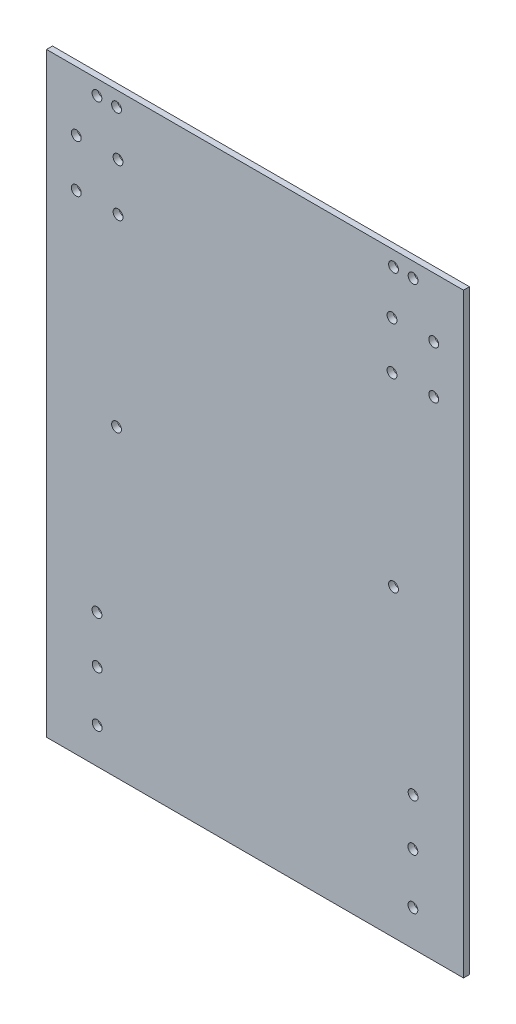
SolidWorks part; units mm, degrees
ref_plane "前视基准面" through (0, 0, 0) normal (0, 0, 1) x (1, 0, 0)
ref_plane "上视基准面" through (0, 0, 0) normal (0, 1, 0) x (1, 0, 0)
ref_plane "右视基准面" through (0, 0, 0) normal (1, 0, 0) x (0, 0, -1)
sketch "草图1" plane through (0, 0, 0) normal (0, 0, 1) x (1, 0, 0)
  line L1 (-34.1847, 39.4892) -> (105.8153, 39.4892)
  line L2 (-34.1847, 39.4892) -> (-34.1847, -160.5108)
  line L3 (-34.1847, -160.5108) -> (105.8153, -160.5108)
  line L4 (105.8153, 39.4892) -> (105.8153, -160.5108)
  dimension "D1" = 140
  dimension "D2" = 200
extrude "凸台-拉伸1" add sketch "草图1" along normal blind 2
sketch "草图3" plane through (0, 0, 2) normal (0, 0, 1) x (1, 0, 0)
  line L0 (35.8153, 55.5197) -> (35.8153, -164.492) construction
  line L1 (105.8153, 39.4892) -> (-34.1847, 39.4892) construction
  line L2 (127.7344, -12.0108) -> (-49.852, -12.0108) construction
  line L3 (-24.1847, 19.4892) -> (-10.1847, 19.4892) construction
  line L4 (-59.4781, -58.5108) -> (127.7344, -58.5108) construction
  line L5 (-34.1847, 39.4892) -> (-34.1847, -160.5108) construction
  line L6 (-17.1847, 7.5928) -> (-17.1847, -161.4246) construction
  circle A0 centre (-10.6847, 34.4892) radius 1.65
  circle A1 centre (82.3153, 34.4892) radius 1.65
  circle A2 centre (82.3153, -58.5108) radius 1.65
  circle A3 centre (-10.6847, -58.5108) radius 1.65
  circle A4 centre (-24.1847, 19.4892) radius 1.65
  circle A5 centre (-10.1847, 19.4892) radius 1.65
  circle A6 centre (-24.1847, 3.4892) radius 1.65
  circle A7 centre (-10.1847, 3.4892) radius 1.65
  circle A8 centre (81.8153, 3.4892) radius 1.65
  circle A9 centre (95.8153, 3.4892) radius 1.65
  circle A10 centre (81.8153, 19.4892) radius 1.65
  circle A11 centre (95.8153, 19.4892) radius 1.65
  circle A12 centre (-17.1847, -131.5108) radius 1.65
  circle A13 centre (-17.1847, -148.5108) radius 1.65
  circle A14 centre (88.8153, -148.5108) radius 1.65
  circle A15 centre (88.8153, -131.5108) radius 1.65
  circle A16 centre (-17.2547, 34.4892) radius 1.65
  circle A17 centre (88.8853, 34.4892) radius 1.65
  circle A18 centre (88.8853, -115.7208) radius 1.65
  circle A19 centre (-17.2547, -115.7208) radius 1.65
  dimension "D1" = 3.3
  dimension "D5" = 3.3
  dimension "D6" = 3.3
  dimension "D7" = 3.3
  dimension "D8" = 3.3
  dimension "D16" = 3.3
  dimension "D17" = 3.3
  dimension "D19" = 3.3
  dimension "D21" = 3.3
  dimension "D2" = 46.5
  dimension "D3" = 5
  dimension "D4" = 46.5
  dimension "D9" = 16
  dimension "D10" = 16
  dimension "D11" = 14
  dimension "D12" = 20
  dimension "D13" = 14
  dimension "D14" = 10
  dimension "D15" = 10
  dimension "D18" = 90
  dimension "D20" = 53.07
  dimension "D22" = 150.21
extrude "切除-拉伸1" cut sketch "草图3" against normal blind 5
